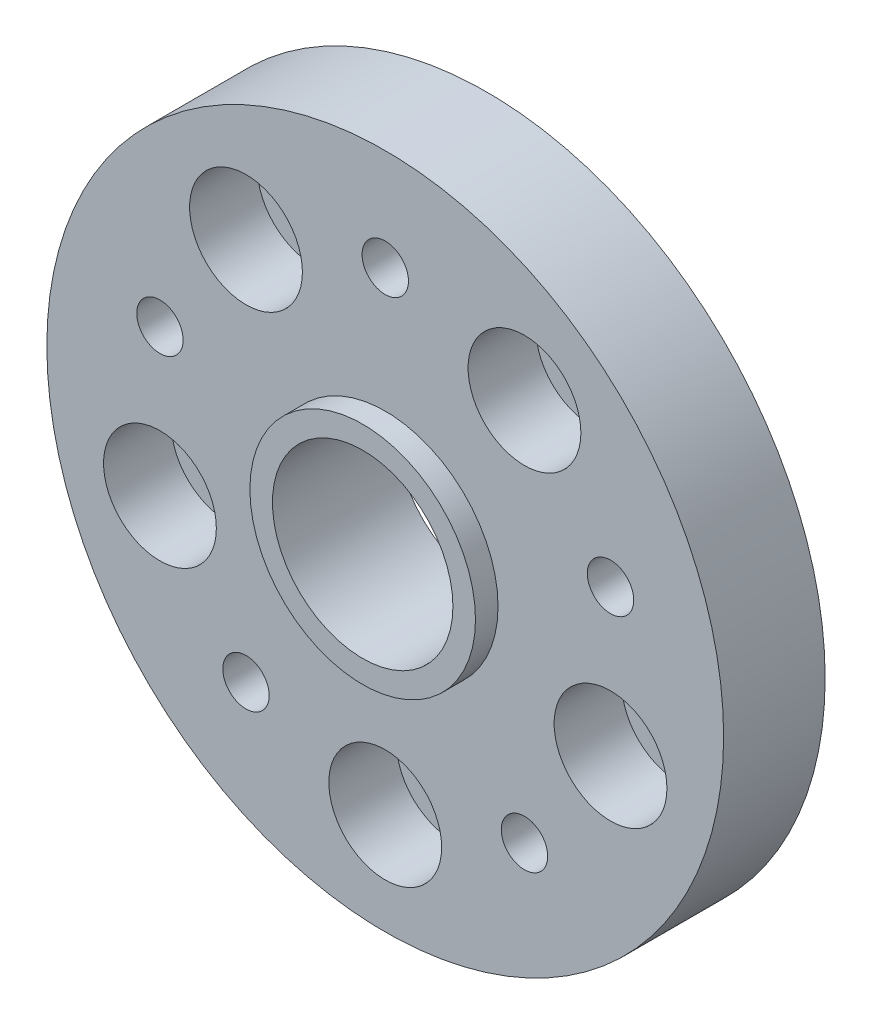
SolidWorks part; units mm, degrees
material "6061-T6 (SS)"
ref_plane "Front Plane" through (0, 0, 0) normal (0, 0, 1) x (1, 0, 0)
ref_plane "Top Plane" through (0, 0, 0) normal (0, 1, 0) x (1, 0, 0)
ref_plane "Right Plane" through (0, 0, 0) normal (1, 0, 0) x (0, 0, -1)
sketch "Sketch1" plane through (0, 0, 0) normal (0, 0, 1) x (1, 0, 0)
  circle A0 centre (0, 0) radius 47.625
  dimension "D1" = 95.25
extrude "Boss-Extrude1" add sketch "Sketch1" along normal blind 14.2875
sketch "Sketch2" plane through (0, 0, 14.2875) normal (0, 0, 1) x (1, 0, 0)
  circle A0 centre (0, 0) radius 12.7
  dimension "D1" = 25.4
extrude "Cut-Extrude1" cut sketch "Sketch2" against normal through all
sketch "Sketch3" plane through (0, 0, 14.2875) normal (0, 0, 1) x (1, 0, 0)
  circle A0 centre (0, 0) radius 15.875
  circle A1 centre (0, 0) radius 12.7
  circle A2 centre (0, 0) radius 12.7 construction
  dimension "D1" = 3.175
extrude "Boss-Extrude2" add sketch "Sketch3" along normal blind 3.175
hole_wizard "CBORE for 3/8 Socket Head Cap Screw1" positions "Sketch6" profile "Sketch7" counterbore size "3/8" standard "ANSI Inch" end condition through all
sketch "Sketch6" plane through (0, 0, 14.2875) normal (0, 0, 1) x (1, 0, 0)
  line L0 (0, 0) -> (0, -33.3375) construction
  point P0 (0, -33.3375)
  point P15 (-31.7058, -10.3019)
  point P16 (-19.5953, 26.9706)
  point P17 (19.5953, 26.9706)
  point P18 (31.7058, -10.3019)
  point P19 (0, 0)
  dimension "D1" = 33.3375
  dimension "D2" = 5
sketch "Sketch7" plane through (0, -33.3375, 14.2875) normal (1, 0, 0) x (0, -1, 0)
  line L0 (0, 0) -> (0, 14.2875)
  line L1 (0, 14.2875) -> (5.0419, 14.2875)
  line L3 (5.0419, 14.2875) -> (5.0419, 9.525)
  line L4 (5.0419, 9.525) -> (7.9375, 9.525)
  line L5 (7.9375, 9.525) -> (7.9375, 0)
  line L7 (7.9375, 0) -> (0, 0)
  line L11 (0, -6.35) -> (0, 107.95) construction
  dimension "Thru Hole Dia." = 10.0838
  dimension "Thru Hole Depth" = 14.2875
  dimension "C'Bore Dia." = 15.875
  dimension "C'Bore Depth" = 9.525
hole_wizard "5/16-18 Tapped Hole1" positions "Sketch8" profile "Sketch9" tap size "5/16-18" standard "ANSI Inch" end condition through all
sketch "Sketch8" plane through (0, 0, 14.2875) normal (0, 0, 1) x (1, 0, 0)
  line L0 (0, 0) -> (0, -33.3375) construction
  line L1 (0, 0) -> (-19.5953, -26.9706) construction
  point P0 (-19.5953, -26.9706)
  point P20 (-31.7058, 10.3019)
  point P21 (0, 33.3375)
  point P22 (31.7058, 10.3019)
  point P23 (19.5953, -26.9706)
  point P24 (0, 0)
  dimension "D1" = 36
  dimension "D2" = 5
sketch "Sketch9" plane through (-19.5953, -26.9706, 14.2875) normal (1, 0, 0) x (0, -1, 0)
  line L0 (0, 0) -> (0, 14.2875)
  line L1 (0, 14.2875) -> (3.2639, 14.2875)
  line L2 (3.2639, 14.2875) -> (3.2639, 0)
  line L5 (3.2639, 0) -> (0, 0)
  line L11 (0, -6.35) -> (0, 107.95) construction
  dimension "Thru Tap Drill Dia." = 6.5278
  dimension "Thru Tap Drill Depth" = 14.2875
cosmetic thread "Hole Thread1"
cosmetic thread "Hole Thread2"
cosmetic thread "Hole Thread3"
cosmetic thread "Hole Thread4"
cosmetic thread "Hole Thread5"
